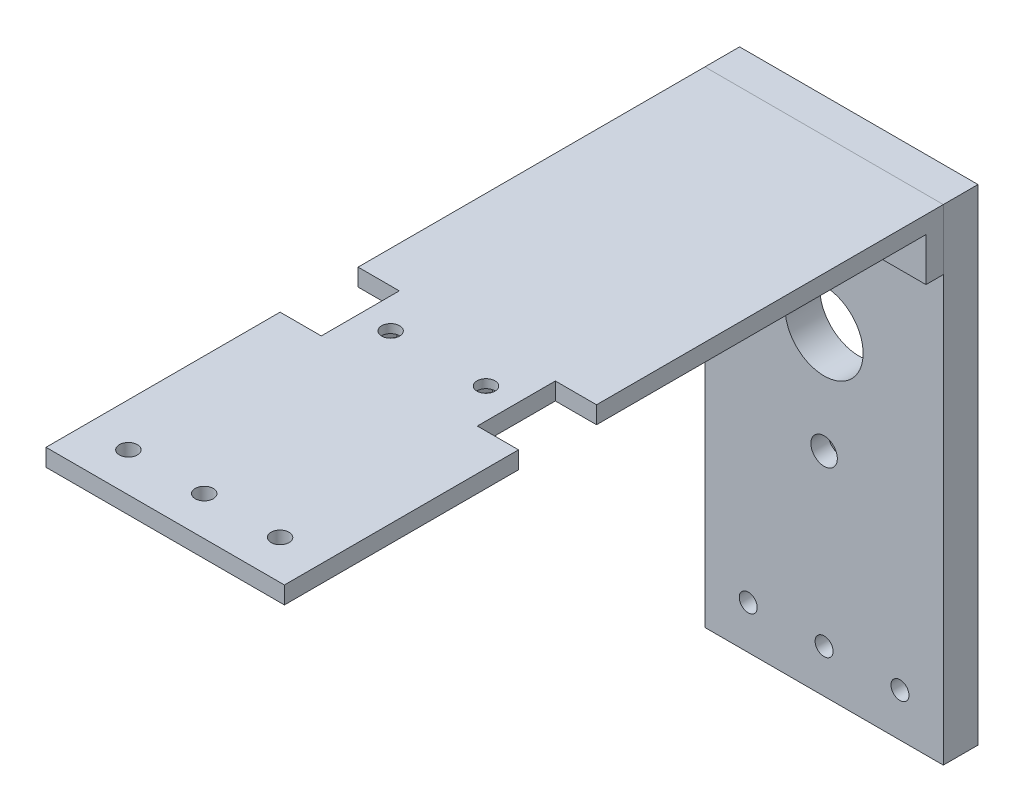
SolidWorks part; units mm, degrees
ref_plane "Front Plane" through (0, 0, 0) normal (0, 0, 1) x (1, 0, 0)
ref_plane "Top Plane" through (0, 0, 0) normal (0, 1, 0) x (1, 0, 0)
ref_plane "Right Plane" through (0, 0, 0) normal (1, 0, 0) x (0, 0, -1)
sketch "Sketch1" plane through (0, 0, 0) normal (1, 0, 0) x (0, 0, -1)
  line L0 (0, 0) -> (160, 0)
  line L1 (160, 0) -> (160, -112)
  line L2 (160, -112) -> (152, -112)
  line L3 (152, -112) -> (152, -4)
  line L4 (152, -4) -> (0, -4)
  line L5 (0, -4) -> (0, 0)
  dimension "D1" = 160
  dimension "D2" = 112
  dimension "D3" = 8
  dimension "D4" = 4
extrude "Boss-Extrude1" add sketch "Sketch1" along normal blind 55
sketch "Sketch2" plane through (0, 0, -160) normal (0, 0, -1) x (-1, 0, 0)
  line L0 (-27.5, 0) -> (-27.5, -39) construction
  line L1 (-55, 0) -> (0, 0) construction
  line L2 (-27.5, -39) -> (-27.5, -63) construction
  line L3 (-27.5, -39) -> (-52.4717, -39) construction
  circle A0 centre (-27.5, -39) radius 9
  circle A1 centre (-27.5, -63) radius 3.05
  circle A2 centre (-27.5, -15) radius 3.05
  dimension "D2" = 18
  dimension "D4" = 6.1
  dimension "D1" = 39
  dimension "D3" = 24
extrude "Cut-Extrude1" cut sketch "Sketch2" against normal up to next
sketch "Sketch3" plane through (0, 0, -160) normal (0, 0, -1) x (-1, 0, 0)
  line L0 (-55, 0) -> (0, 0) construction
  line L1 (-21.7265, -15) -> (-24.6132, -10)
  line L2 (-24.6132, -10) -> (-30.3868, -10)
  line L3 (-30.3868, -10) -> (-33.2735, -15)
  line L4 (-33.2735, -15) -> (-30.3868, -20)
  line L5 (-30.3868, -20) -> (-24.6132, -20)
  line L6 (-24.6132, -20) -> (-21.7265, -15)
  line L7 (-24.6132, -68) -> (-21.7265, -63)
  line L8 (-21.7265, -63) -> (-24.6132, -58)
  line L9 (-24.6132, -58) -> (-30.3868, -58)
  line L10 (-30.3868, -58) -> (-33.2735, -63)
  line L11 (-33.2735, -63) -> (-30.3868, -68)
  line L12 (-30.3868, -68) -> (-24.6132, -68)
  circle A0 centre (-27.5, -15) radius 5 construction
  circle A1 centre (-27.5, -63) radius 5 construction
  dimension "D1" = 10
  dimension "D2" = 10
extrude "Cut-Extrude2" cut sketch "Sketch3" against normal blind 4
sketch "Sketch4" plane through (0, 0, 0) normal (0, 1, 0) x (1, 0, 0)
  line L0 (55, 160) -> (38.5, 160) construction
  line L1 (55, 160) -> (0, 160) construction
  line L2 (38.5, 160) -> (38.5, 63) construction
  line L3 (27.5, 160) -> (27.5, 19.9309) construction
  circle A0 centre (38.5, 63) radius 2.075
  circle A1 centre (16.5, 63) radius 2.075
  dimension "D3" = 4.15
  dimension "D1" = 16.5
  dimension "D2" = 97
extrude "Cut-Extrude3" cut sketch "Sketch4" against normal blind 4
sketch "Sketch7" plane through (0, -4, 0) normal (0, -1, 0) x (-1, 0, 0)
  line L0 (-55, 0) -> (0, 0) construction
  line L1 (-18.5207, 66.5) -> (-20.5415, 63)
  line L2 (-20.5415, 63) -> (-18.5207, 59.5)
  line L3 (-18.5207, 59.5) -> (-14.4793, 59.5)
  line L4 (-14.4793, 59.5) -> (-12.4585, 63)
  line L5 (-12.4585, 63) -> (-14.4793, 66.5)
  line L6 (-14.4793, 66.5) -> (-18.5207, 66.5)
  line L7 (-42.5415, 63) -> (-40.5207, 59.5)
  line L8 (-40.5207, 59.5) -> (-36.4793, 59.5)
  line L9 (-36.4793, 59.5) -> (-34.4585, 63)
  line L10 (-34.4585, 63) -> (-36.4793, 66.5)
  line L11 (-36.4793, 66.5) -> (-40.5207, 66.5)
  line L12 (-40.5207, 66.5) -> (-42.5415, 63)
  circle A0 centre (-16.5, 63) radius 3.5 construction
  circle A1 centre (-38.5, 63) radius 3.5 construction
  dimension "D1" = 7
  dimension "D2" = 7
extrude "Cut-Extrude5" cut sketch "Sketch7" against normal blind 2
sketch "Sketch8" plane through (0, 0, 0) normal (0, 1, 0) x (1, 0, 0)
  line L0 (0, 160) -> (0, 72) construction
  line L1 (0, 160) -> (0, 0) construction
  line L2 (27.5, 160) -> (27.5, 81.66) construction
  line L3 (0, 72) -> (9.5, 72)
  line L4 (0, 72) -> (0, 54)
  line L5 (0, 54) -> (9.5, 54)
  line L6 (9.5, 72) -> (9.5, 54)
  line L7 (55, 160) -> (0, 160) construction
  line L8 (45.5, 72) -> (45.5, 54)
  line L9 (55, 54) -> (45.5, 54)
  line L10 (55, 72) -> (55, 54)
  line L11 (55, 72) -> (45.5, 72)
  dimension "D1" = 88
  dimension "D2" = 9.5
  dimension "D3" = 18
extrude "Cut-Extrude6" cut sketch "Sketch8" against normal up to next
sketch "Sketch9" plane through (0, 0, -160) normal (0, 0, -1) x (-1, 0, 0)
  line L0 (-55, -112) -> (-45, -112) construction
  line L1 (-55, -112) -> (0, -112) construction
  line L2 (-45, -112) -> (-45, -102) construction
  line L3 (-45, -102) -> (-27.5, -102) construction
  line L4 (-27.5, -102) -> (-10, -102) construction
  circle A0 centre (-45, -102) radius 2.075
  circle A1 centre (-27.5, -102) radius 2.075
  circle A2 centre (-10, -102) radius 2.075
  dimension "D3" = 4.15
  dimension "D6" = 4.15
  dimension "D7" = 4.15
  dimension "D1" = 10
  dimension "D2" = 10
  dimension "D4" = 17.5
  dimension "D5" = 17.5
extrude "Cut-Extrude7" cut sketch "Sketch9" against normal up to next
sketch "Sketch10" plane through (0, 0, 0) normal (0, 1, 0) x (1, 0, 0)
  line L0 (0, 0) -> (0, 9) construction
  line L1 (0, 54) -> (0, 0) construction
  line L2 (0, 9) -> (10, 9) construction
  line L3 (10, 9) -> (27.5, 9) construction
  line L4 (27.5, 9) -> (45, 9) construction
  circle A0 centre (10, 9) radius 2.075
  circle A1 centre (27.5, 9) radius 2.075
  circle A2 centre (45, 9) radius 2.075
  dimension "D5" = 4.15
  dimension "D6" = 4.15
  dimension "D7" = 4.15
  dimension "D1" = 9
  dimension "D2" = 10
  dimension "D3" = 17.5
  dimension "D4" = 17.5
extrude "Cut-Extrude8" cut sketch "Sketch10" against normal up to next
sketch "Sketch12" plane through (0, -4, 0) normal (0, -1, 0) x (1, 0, 0)
  line L0 (55, -72) -> (55, -152) construction
  line L1 (0, -152) -> (55, -152)
  line L2 (0, -152) -> (0, -148)
  line L3 (0, -148) -> (55, -148)
  line L4 (55, -152) -> (55, -148)
  dimension "D1" = 55
  dimension "D2" = 4
extrude "Boss-Extrude2" add sketch "Sketch12" along normal blind 10 contours L3 L4 L1 L2
sketch "Sketch13" plane through (0, 0, -148) normal (0, 0, 1) x (1, 0, 0)
  line L0 (0, -14) -> (16, -14) construction
  line L1 (0, -14) -> (55, -14) construction
  line L3 (16, -14) -> (39, -14)
  line L4 (16, -14) -> (16, -7)
  line L5 (16, -7) -> (39, -7)
  line L6 (39, -14) -> (39, -7)
  dimension "D1" = 16
  dimension "D2" = 7
  dimension "D3" = 23
extrude "Cut-Extrude9" cut sketch "Sketch13" against normal blind 4
sketch "Sketch14" plane through (0, 0, -148) normal (0, 0, 1) x (1, 0, 0)
  line L0 (0, -9) -> (8, -9) construction
  line L1 (0, -14) -> (0, -4) construction
  line L2 (27.5, -7) -> (27.5, -4) construction
  line L3 (39, -7) -> (16, -7) construction
  line L4 (55, -4) -> (0, -4) construction
  circle A0 centre (8, -9) radius 2.075
  circle A1 centre (47, -9) radius 2.075
  dimension "D2" = 4.15
  dimension "D1" = 8
extrude "Cut-Extrude10" cut sketch "Sketch14" against normal up to next
sketch "Sketch15" plane through (0, 0, -160) normal (0, 0, -1) x (-1, 0, 0)
  line L0 (-55, 0) -> (0, 0) construction
  line L1 (-42.9585, -9) -> (-44.9793, -5.5)
  line L2 (-44.9793, -5.5) -> (-49.0207, -5.5)
  line L3 (-49.0207, -5.5) -> (-51.0415, -9)
  line L4 (-51.0415, -9) -> (-49.0207, -12.5)
  line L5 (-49.0207, -12.5) -> (-44.9793, -12.5)
  line L6 (-44.9793, -12.5) -> (-42.9585, -9)
  line L7 (-3.9585, -9) -> (-5.9793, -5.5)
  line L8 (-5.9793, -5.5) -> (-10.0207, -5.5)
  line L9 (-10.0207, -5.5) -> (-12.0415, -9)
  line L10 (-12.0415, -9) -> (-10.0207, -12.5)
  line L11 (-10.0207, -12.5) -> (-5.9793, -12.5)
  line L12 (-5.9793, -12.5) -> (-3.9585, -9)
  circle A0 centre (-47, -9) radius 3.5 construction
  circle A1 centre (-8, -9) radius 3.5 construction
  dimension "D1" = 7
  dimension "D2" = 7
extrude "Cut-Extrude11" cut sketch "Sketch15" against normal blind 3.2
sketch "Sketch16" plane through (0, 0, 0) normal (-1, 0, 0) x (0, 0, 1)
  line L0 (-152, -14) -> (-152, 0)
  line L1 (-160, 0) -> (-72, 0) construction
split "Split1" trim tools "Sketch16" bodies to split 113 resulting bodies 114 115
